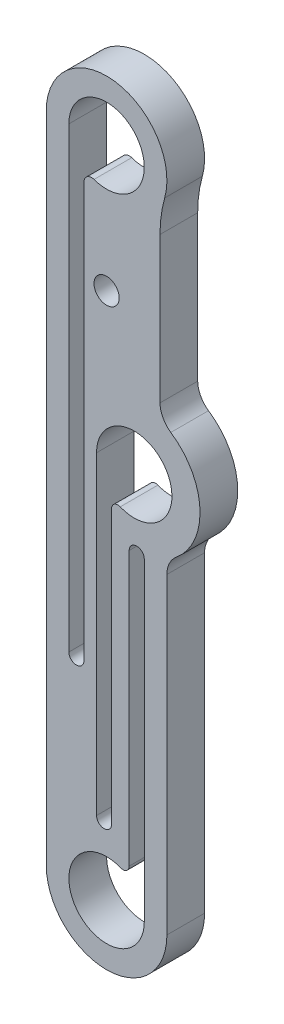
SolidWorks part; units mm, degrees
ref_plane "前视基准面" through (0, 0, 0) normal (0, 0, 1) x (1, 0, 0)
ref_plane "上视基准面" through (0, 0, 0) normal (0, 1, 0) x (1, 0, 0)
ref_plane "右视基准面" through (0, 0, 0) normal (1, 0, 0) x (0, 0, -1)
sketch "草图1" plane through (0, 0, 0) normal (0, 0, 1) x (1, 0, 0)
  line L0 (-379.176, 79.3777) -> (-379.176, 89.3777) construction
  line L1 (-374.9267, 73.771) -> (-374.9267, 85.378)
  line L2 (-374.376, 37.3777) -> (-374.376, 62.2241)
  line L3 (-383.976, 52.2255) -> (-383.976, 37.3777)
  line L4 (-383.976, 89.3777) -> (-383.976, 52.2255)
  line L5 (-382.176, 89.3777) -> (-382.176, 52.9799)
  line L6 (-380.976, 52.9799) -> (-380.976, 85.9644)
  line L7 (-378.776, 42.8111) -> (-378.776, 64.5615)
  line L8 (-379.976, 67.8111) -> (-379.976, 42.8111)
  line L9 (-376.176, 37.3777) -> (-376.176, 62.3777)
  line L11 (-377.376, 62.3777) -> (-377.376, 40.6273)
  arc A0 (-376.176, 62.3777) -> (-377.376, 62.3777) centre (-376.776, 62.3777) ccw
  arc A1 (-374.5546, 88.0805) -> (-374.9267, 85.378) centre (-364.9267, 85.378) ccw
  arc A2 (-374.9267, 73.771) -> (-374.0665, 72.1655) centre (-372.927, 73.8092) ccw
  arc A3 (-373.6472, 63.7681) -> (-374.0665, 72.1655) centre (-376.976, 67.8111) ccw
  arc A4 (-373.6472, 63.7681) -> (-374.376, 62.2241) centre (-372.376, 62.2241) ccw
  arc A5 (-383.976, 37.3777) -> (-374.376, 37.3777) centre (-379.176, 37.3777) ccw
  arc A7 (-380.176, 86.5493) -> (-380.976, 85.9644) centre (-380.3621, 85.9644) ccw
  arc A8 (-380.176, 86.5493) -> (-382.176, 89.3777) centre (-379.176, 89.3777) ccw
  arc A9 (-382.176, 52.9799) -> (-380.976, 52.9799) centre (-381.576, 52.9799) ccw
  arc A10 (-379.976, 42.8111) -> (-378.776, 42.8111) centre (-379.376, 42.8111) ccw
  arc A11 (-378.0902, 65.0257) -> (-378.776, 64.5615) centre (-378.276, 64.5615) ccw
  arc A12 (-378.0902, 65.0257) -> (-379.976, 67.8111) centre (-376.976, 67.8111) ccw
  arc A13 (-378.0617, 40.1631) -> (-376.176, 37.3777) centre (-379.176, 37.3777) ccw
  arc A14 (-377.376, 40.6273) -> (-378.0617, 40.1631) centre (-377.876, 40.6273) cw
  arc A15 (-374.5546, 88.0805) -> (-383.976, 89.3777) centre (-379.176, 89.3777) ccw
  circle A16 centre (-379.176, 79.3777) radius 1
  dimension "D3" = 0.6
  dimension "D6" = 1.8
  dimension "D7" = 0.5
  dimension "D8" = 10
  dimension "D9" = 52
  dimension "D10" = 2
  dimension "D1" = 21.5666
  dimension "D2" = 25
  dimension "D4" = 25
  dimension "D5" = 1.8
  dimension "D11" = 10
extrude "凸台-拉伸1" add sketch "草图1" along normal blind 3
